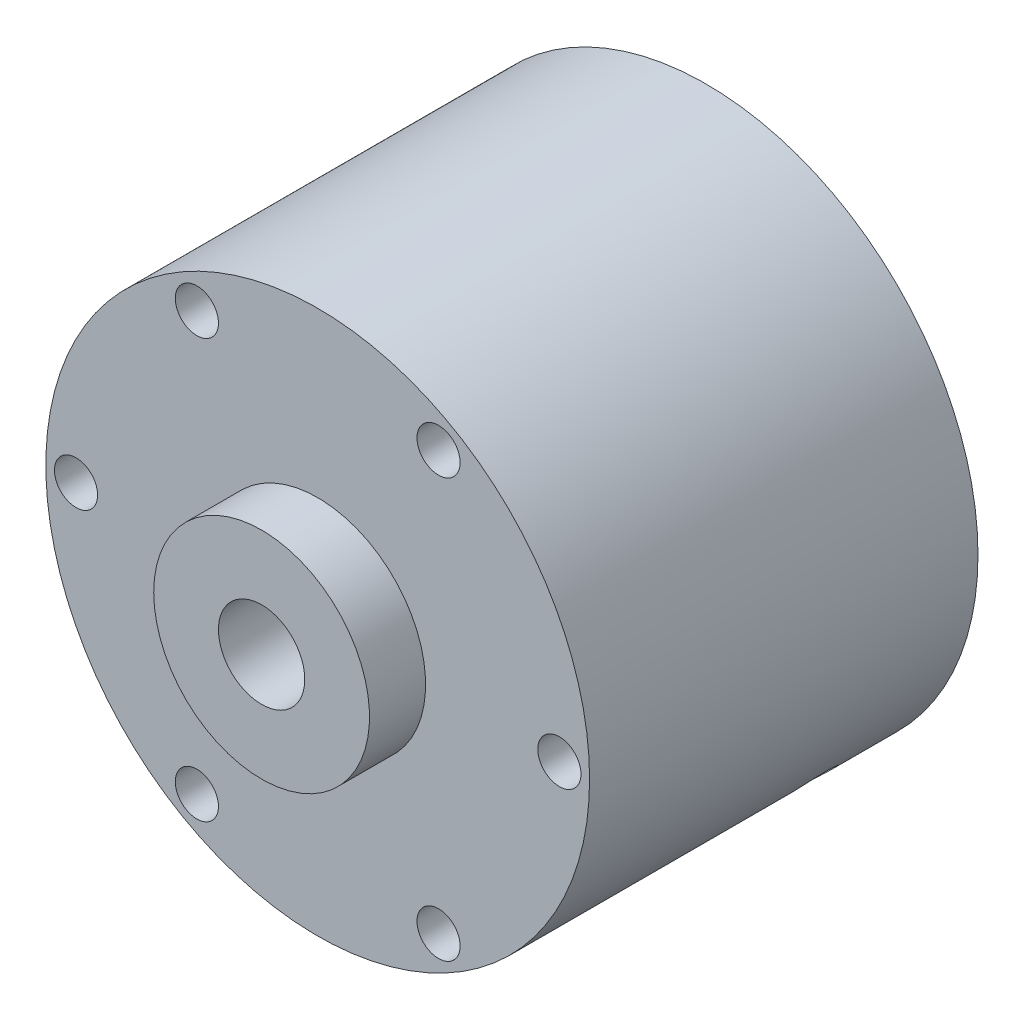
SolidWorks part; units mm, degrees
material "6061 合金"
ref_plane "前视基准面" through (0, 0, 0) normal (0, 0, 1) x (1, 0, 0)
ref_plane "上视基准面" through (0, 0, 0) normal (0, 1, 0) x (1, 0, 0)
ref_plane "右视基准面" through (0, 0, 0) normal (1, 0, 0) x (0, 0, -1)
sketch "草图2" plane through (0, 0, 0) normal (0, 0, 1) x (1, 0, 0)
  circle A0 centre (0, 0) radius 12.5
  dimension "D1" = 25
extrude "凸台-拉伸1" add sketch "草图2" along normal blind 1.5
sketch "草图3" plane through (0, 0, 1.5) normal (0, 0, 1) x (1, 0, 0)
  circle A0 centre (0, 0) radius 31.5
  dimension "D1" = 63
extrude "凸台-拉伸2" add sketch "草图3" along normal blind 45
sketch "草图4" plane through (0, 0, 46.5) normal (0, 0, 1) x (1, 0, 0)
  circle A0 centre (0, 0) radius 12.5
  dimension "D1" = 25
extrude "凸台-拉伸3" add sketch "草图4" along normal blind 6.5
sketch "草图5" plane through (0, 0, 53) normal (0, 0, 1) x (1, 0, 0)
  circle A0 centre (0, 0) radius 5
  dimension "D1" = 10
extrude "切除-拉伸1" cut sketch "草图5" against normal through all
ref_plane "基准面1" through (0, 0, 0) normal (-0.7071, 0.7071, 0) x (0.7071, 0.7071, 0)
sketch "草图6" plane through (0, 0, 0) normal (-0.7071, 0.7071, 0) x (0.7071, 0.7071, 0)
  line L0 (31.5, -1.5) -> (-31.5, -1.5) construction
  circle A0 centre (0, -11.5) radius 2.5
  dimension "D1" = 10
  dimension "D2" = 5
extrude "切除-拉伸2" cut sketch "草图6" against normal through all
sketch "草图7" plane through (0, 0, 0) normal (0, 1, 0) x (1, 0, 0)
  line L0 (31.5, -1.5) -> (-31.5, -1.5) construction
  circle A0 centre (0, -11.5) radius 2.5
  dimension "D1" = 10
  dimension "D2" = 5
extrude "切除-拉伸3" cut sketch "草图7" against normal through all
sketch "草图8" plane through (0, 0, 46.5) normal (0, 0, 1) x (1, 0, 0)
  circle A0 centre (0, 0) radius 28 construction
  circle A1 centre (28, 0) radius 2.5
  circle A2 centre (-14, -24.2487) radius 2.5
  circle A3 centre (-14, 24.2487) radius 2.5
  point P12 (0, 0)
  dimension "D1" = 56
  dimension "D2" = 5
  dimension "D3" = 3
extrude "切除-拉伸4" cut sketch "草图8" against normal blind 10
cosmetic thread "装饰螺纹线1" parameters "D2"=6
cosmetic thread "装饰螺纹线3" parameters "D2"=6
cosmetic thread "装饰螺纹线5" parameters "D2"=6
sketch "草图9" plane through (0, 0, 46.5) normal (0, 0, 1) x (1, 0, 0)
  circle A0 centre (0, 0) radius 28 construction
  circle A1 centre (-28, 0) radius 2.5
  circle A2 centre (14, 24.2487) radius 2.5
  circle A3 centre (14, -24.2487) radius 2.5
  point P12 (0, 0)
  dimension "D1" = 56
  dimension "D2" = 5
  dimension "D3" = 3
extrude "切除-拉伸5" cut sketch "草图9" against normal blind 16
cosmetic thread "装饰螺纹线2" parameters "D2"=6
cosmetic thread "装饰螺纹线4" parameters "D2"=6
cosmetic thread "装饰螺纹线6" parameters "D2"=6
